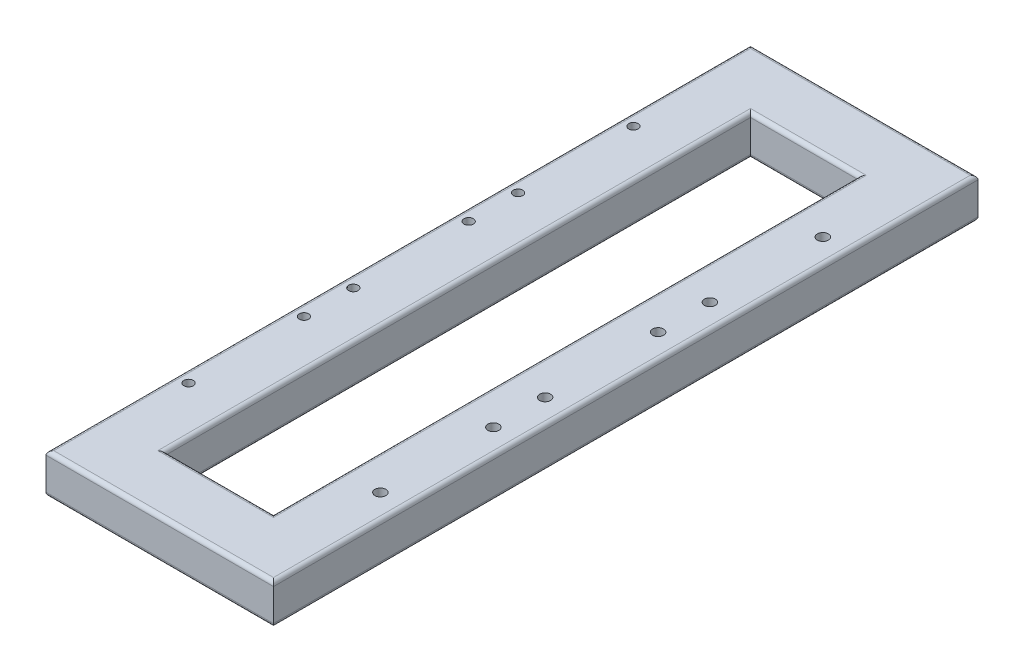
SolidWorks part; units mm, degrees
ref_plane "Alzado" through (0, 0, 0) normal (0, 0, 1) x (1, 0, 0)
ref_plane "Planta" through (0, 0, 0) normal (0, 1, 0) x (1, 0, 0)
ref_plane "Vista lateral" through (0, 0, 0) normal (1, 0, 0) x (0, 0, -1)
sketch "Croquis1" plane through (0, 0, 0) normal (0, 1, 0) x (1, 0, 0)
  line L0 (-273.75, 375.5) -> (-273.75, 312.5) construction
  line L1 (-290, 0) -> (0, 0)
  line L2 (-290, 0) -> (-290, 898)
  line L3 (-290, 898) -> (0, 898)
  line L4 (0, 0) -> (0, 898)
  line L5 (-290, 0) -> (0, 898) construction
  line L6 (-290, 898) -> (0, 0) construction
  line L7 (-213.8, 76.2) -> (-76.2, 76.2)
  line L8 (-213.8, 76.2) -> (-213.8, 821.8)
  line L9 (-213.8, 821.8) -> (-76.2, 821.8)
  line L10 (-76.2, 76.2) -> (-76.2, 821.8)
  line L11 (-213.8, 76.2) -> (-76.2, 821.8) construction
  line L12 (-213.8, 821.8) -> (-76.2, 76.2) construction
  line L13 (-30.75, 377) -> (-30.75, 311) construction
  line L14 (-273.75, 312.5) -> (-273.75, 165.5) construction
  line L15 (-30.75, 311) -> (-30.75, 167) construction
  line L16 (-145, 449) -> (-442.0409, 449) construction
  line L17 (-30.75, 587) -> (-30.75, 731) construction
  line L18 (-273.75, 585.5) -> (-273.75, 732.5) construction
  circle A0 centre (-273.75, 375.5) radius 6
  circle A1 centre (-273.75, 522.5) radius 6
  circle A2 centre (-30.75, 377) radius 7
  circle A3 centre (-30.75, 521) radius 7
  circle A4 centre (-30.75, 167) radius 7
  circle A5 centre (-273.75, 732.5) radius 6
  circle A6 centre (-273.75, 312.5) radius 6
  circle A7 centre (-30.75, 311) radius 7
  circle A8 centre (-273.75, 165.5) radius 6
  circle A9 centre (-30.75, 587) radius 7
  circle A10 centre (-273.75, 585.5) radius 6
  circle A11 centre (-30.75, 731) radius 7
  point P0 (-145, 449)
  point P5 (-145, 449)
  point P36 (0, 0)
  point P39 (0, 0)
  dimension "D3" = 14
  dimension "D4" = 12
  dimension "D7" = 14
  dimension "D15" = 63
  dimension "D16" = 66
  dimension "D17" = 73.5
  dimension "D1" = 63
  dimension "D2" = 66
  dimension "D5" = 147
  dimension "D6" = 144
  dimension "D8" = 290
  dimension "D9" = 898
  dimension "D10" = 76.2
  dimension "D11" = 76.2
  dimension "D12" = 167
  dimension "D13" = 30.75
  dimension "D14" = 16.25
  dimension "D18" = 72
  dimension "D19" = 73.5
  dimension "D20" = 72
extrude "Saliente-Extruir1" add sketch "Croquis1" along normal blind 50.8
fillet "Redondeo1" radius 5 8 edges at (0, 50.8, -449) (-145, 50.8, -898) (-290, 50.8, -449) (-145, 50.8, 0) (-145, 50.8, -76.2) (-76.2, 50.8, -449) (-145, 50.8, -821.8) (-213.8, 50.8, -449)
fillet "Redondeo2" radius 5 8 edges at (-145, 0, -898) (-290, 0, -449) (0, 0, -449) (-145, 0, 0) (-145, 0, -76.2) (-213.8, 0, -449) (-145, 0, -821.8) (-76.2, 0, -449)
